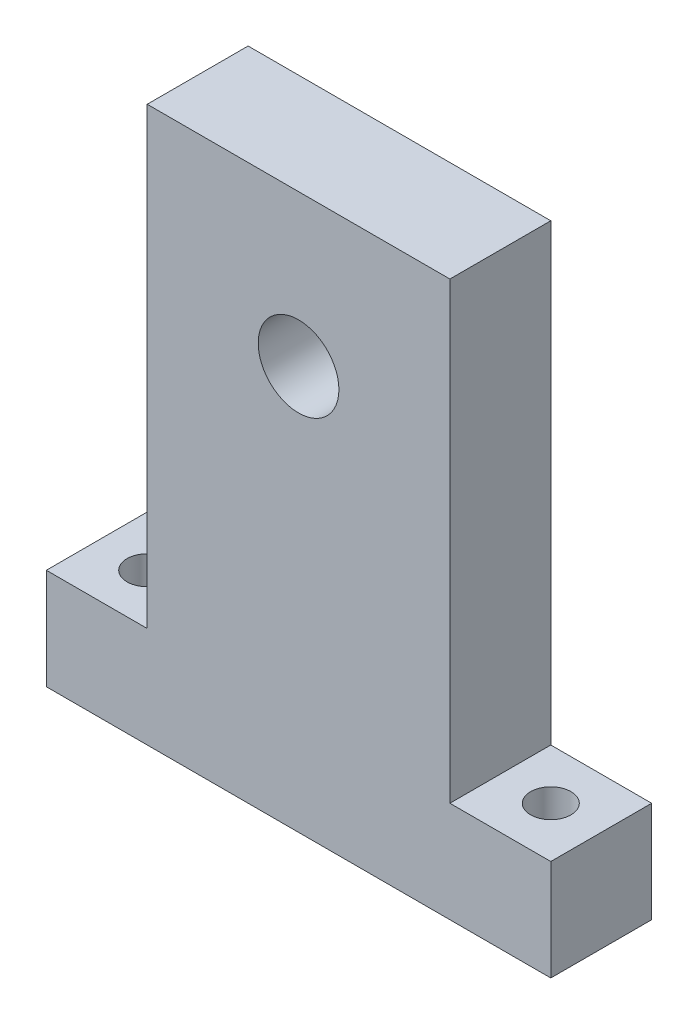
SolidWorks part; units mm, degrees
material "Acrylic (Medium-high impact)"
ref_plane "Front Plane" through (0, 0, 0) normal (0, 0, 1) x (1, 0, 0)
ref_plane "Top Plane" through (0, 0, 0) normal (0, 1, 0) x (1, 0, 0)
ref_plane "Right Plane" through (0, 0, 0) normal (1, 0, 0) x (0, 0, -1)
sketch "Sketch1" plane through (0, 0, 0) normal (0, 1, 0) x (1, 0, 0)
  line L1 (-25, -5) -> (25, -5)
  line L2 (-25, -5) -> (-25, 5)
  line L3 (-25, 5) -> (25, 5)
  line L4 (25, -5) -> (25, 5)
  line L5 (-25, -5) -> (25, 5) construction
  line L6 (-25, 5) -> (25, -5) construction
  circle A0 centre (-20, 0) radius 2
  circle A1 centre (20, 0) radius 2
  point P0 (0, 0)
  dimension "D3" = 4
  dimension "D4" = 4
  dimension "D1" = 10
  dimension "D2" = 50
  dimension "D5" = 20
  dimension "D6" = 20
extrude "Boss-Extrude1" add sketch "Sketch1" along normal blind 10 contours L1 L4 L3 L2
sketch "Sketch4" plane through (0, 10, 0) normal (0, 1, 0) x (1, 0, 0)
  line L0 (-25, 5) -> (25, 5) construction
  line L1 (-15, -5) -> (15, -5)
  line L2 (-15, -5) -> (-15, 5)
  line L3 (-15, 5) -> (15, 5)
  line L4 (15, -5) -> (15, 5)
  line L5 (-15, -5) -> (15, 5) construction
  line L6 (-15, 5) -> (15, -5) construction
  point P0 (0, 0)
  dimension "D1" = 30
extrude "Boss-Extrude3" add sketch "Sketch4" along normal blind 45
sketch "Sketch5" plane through (0, 0, 5) normal (0, 0, 1) x (1, 0, 0)
  line L0 (-15, 55) -> (15, 55) construction
  circle A0 centre (0, 40) radius 4
  dimension "D1" = 8
  dimension "D2" = 15
extrude "Cut-Extrude1" cut sketch "Sketch5" against normal blind 45
